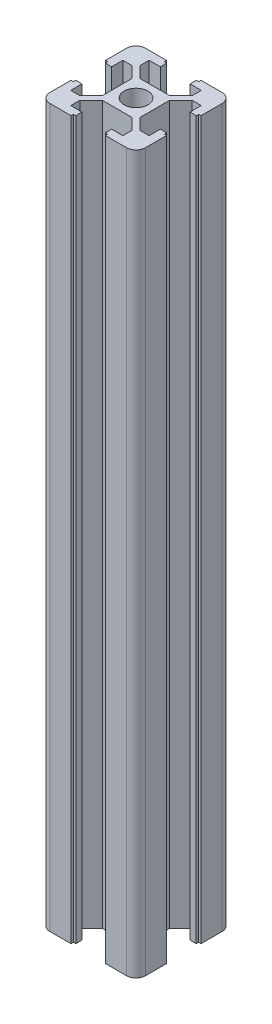
SolidWorks part; units mm, degrees
ref_plane "前视基准面" through (0, 0, 0) normal (0, 0, 1) x (1, 0, 0)
ref_plane "上视基准面" through (0, 0, 0) normal (0, 1, 0) x (1, 0, 0)
ref_plane "右视基准面" through (0, 0, 0) normal (1, 0, 0) x (0, 0, -1)
sketch "草图1" plane through (0, 0, 0) normal (0, 1, 0) x (1, 0, 0)
  line L0 (-6.2985, -5.45) -> (-3.9485, -3.1)
  line L1 (-5.45, -6.2985) -> (-3.1, -3.9485)
  line L2 (-6.2985, -5.45) -> (-8.2, -5.45)
  line L3 (-8.2, -5.45) -> (-8.2, -3.1)
  line L4 (-8.2, -3.1) -> (-10, -3.1)
  line L5 (-10, -3.1) -> (-10, -8)
  line L6 (-8, -10) -> (-3.1, -10)
  line L7 (-5.45, -6.2985) -> (-5.45, -8.2)
  line L8 (-5.45, -8.2) -> (-3.1, -8.2)
  line L9 (-3.1, -8.2) -> (-3.1, -10)
  line L10 (-3.9485, 0) -> (-3.9485, -3.1)
  line L11 (-3.1, -3.9485) -> (0, -3.9485)
  line L12 (-10, -3.6) -> (-9.5, -3.6)
  line L13 (-9.5, -3.6) -> (-9.5, -3.1)
  line L14 (-3.6, -10) -> (-3.6, -9.5)
  line L15 (-3.6, -9.5) -> (-3.1, -9.5)
  line L16 (-3.9485, 0) -> (-2.5, 0) construction
  line L17 (0, -2.5) -> (0, -3.9485) construction
  line L18 (-5.45, 6.2985) -> (-3.1, 3.9485)
  line L19 (-6.2985, 5.45) -> (-3.9485, 3.1)
  line L20 (-5.45, 6.2985) -> (-5.45, 8.2)
  line L21 (-5.45, 8.2) -> (-3.1, 8.2)
  line L22 (-3.1, 8.2) -> (-3.1, 10)
  line L23 (-3.1, 10) -> (-8, 10)
  line L24 (-10, 8) -> (-10, 3.1)
  line L25 (-6.2985, 5.45) -> (-8.2, 5.45)
  line L26 (-8.2, 5.45) -> (-8.2, 3.1)
  line L27 (-8.2, 3.1) -> (-10, 3.1)
  line L28 (-3.1, 3.9485) -> (0, 3.9485)
  line L29 (-3.9485, 3.1) -> (-3.9485, 0)
  line L30 (-3.6, 10) -> (-3.6, 9.5)
  line L31 (-3.6, 9.5) -> (-3.1, 9.5)
  line L32 (-10, 3.6) -> (-9.5, 3.6)
  line L33 (-9.5, 3.6) -> (-9.5, 3.1)
  line L34 (0, 3.9485) -> (0, 2.5) construction
  line L35 (-2.5, 0) -> (-3.9485, 0) construction
  line L36 (6.2985, 5.45) -> (3.9485, 3.1)
  line L37 (5.45, 6.2985) -> (3.1, 3.9485)
  line L38 (6.2985, 5.45) -> (8.2, 5.45)
  line L39 (8.2, 5.45) -> (8.2, 3.1)
  line L40 (8.2, 3.1) -> (10, 3.1)
  line L41 (10, 3.1) -> (10, 8)
  line L42 (8, 10) -> (3.1, 10)
  line L43 (5.45, 6.2985) -> (5.45, 8.2)
  line L44 (5.45, 8.2) -> (3.1, 8.2)
  line L45 (3.1, 8.2) -> (3.1, 10)
  line L46 (3.9485, 0) -> (3.9485, 3.1)
  line L47 (3.1, 3.9485) -> (0, 3.9485)
  line L48 (10, 3.6) -> (9.5, 3.6)
  line L49 (9.5, 3.6) -> (9.5, 3.1)
  line L50 (3.6, 10) -> (3.6, 9.5)
  line L51 (3.6, 9.5) -> (3.1, 9.5)
  line L52 (3.9485, 0) -> (2.5, 0) construction
  line L53 (0, 2.5) -> (0, 3.9485) construction
  line L54 (5.45, -6.2985) -> (3.1, -3.9485)
  line L55 (6.2985, -5.45) -> (3.9485, -3.1)
  line L56 (5.45, -6.2985) -> (5.45, -8.2)
  line L57 (5.45, -8.2) -> (3.1, -8.2)
  line L58 (3.1, -8.2) -> (3.1, -10)
  line L59 (3.1, -10) -> (8, -10)
  line L60 (10, -8) -> (10, -3.1)
  line L61 (6.2985, -5.45) -> (8.2, -5.45)
  line L62 (8.2, -5.45) -> (8.2, -3.1)
  line L63 (8.2, -3.1) -> (10, -3.1)
  line L64 (0, -3.9485) -> (3.1, -3.9485)
  line L65 (3.9485, -3.1) -> (3.9485, 0)
  line L66 (3.6, -10) -> (3.6, -9.5)
  line L67 (3.6, -9.5) -> (3.1, -9.5)
  line L68 (10, -3.6) -> (9.5, -3.6)
  line L69 (9.5, -3.6) -> (9.5, -3.1)
  line L70 (0, -3.9485) -> (0, -2.5) construction
  line L71 (2.5, 0) -> (3.9485, 0) construction
  line L72 (0, 3.9485) -> (-3.1, 3.9485) [skipped]
  circle A0 centre (0, 0) radius 2.5
  arc A1 (-10, -8) -> (-8, -10) centre (-8, -8) ccw
  arc A3 (-8, 10) -> (-10, 8) centre (-8, 8) ccw
  arc A5 (10, 8) -> (8, 10) centre (8, 8) ccw
  arc A7 (8, -10) -> (10, -8) centre (8, -8) ccw
  point P25 (-10, -10)
  point P98 (0, 0)
  dimension "D9" = 2
  dimension "D15" = 5
  dimension "D2" = 1.2
  dimension "D4" = 5.45
  dimension "D5" = 1.8
  dimension "D6" = 3.1
  dimension "D7" = 135
  dimension "D10" = 0.5
  dimension "D11" = 0.5
  dimension "D12" = 0.5
  dimension "D13" = 0.5
  dimension "D14" = 4
extrude "凸台-拉伸1" add sketch "草图1" along normal blind 150 contours L59 A7 L60 L68 L69 L63 L62 L61 L55 L65 L46 L36 L38 L39 L40 L49 L48 L41 A5 L42 L50 L51 L45 L44 L43 L37 L47 L28 L18 L20 L21 L22 L31 L30 L23 A3 L24 L32 L33 L27 L26 L25 L19 L29 L10 L0 L2 L3 L4 L13 L12
